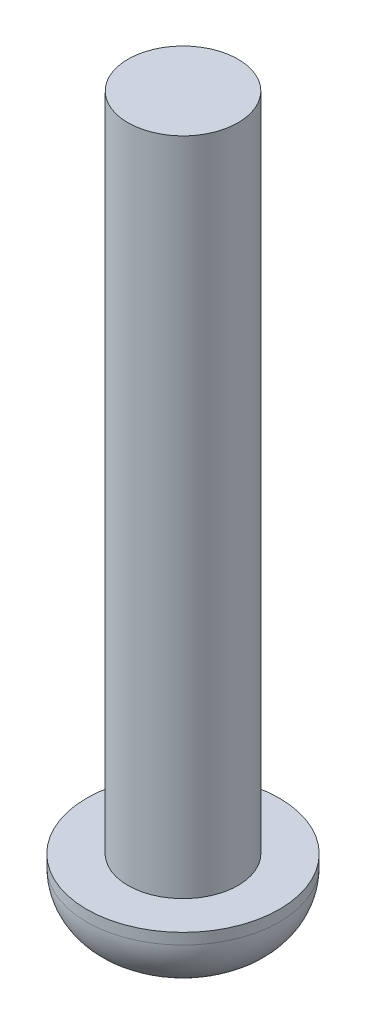
SolidWorks part; units mm, degrees
ref_plane "정면" through (0, 0, 0) normal (0, 0, 1) x (1, 0, 0)
ref_plane "윗면" through (0, 0, 0) normal (0, 1, 0) x (1, 0, 0)
ref_plane "우측면" through (0, 0, 0) normal (1, 0, 0) x (0, 0, -1)
sketch "스케치1" plane through (0, 0, 0) normal (0, 1, 0) x (1, 0, 0)
  circle A0 centre (0, 0) radius 1.75
  dimension "D1" = 3.5
extrude "보스-돌출1" add sketch "스케치1" along normal blind 1.2
sketch "스케치2" plane through (0, 1.2, 0) normal (0, 1, 0) x (1, 0, 0)
  circle A0 centre (0, 0) radius 1
  dimension "D1" = 2
extrude "보스-돌출2" add sketch "스케치2" along normal blind 12 contours A0
fillet "필렛1" radius 1 1 edges at (0, 0, 1.75)
